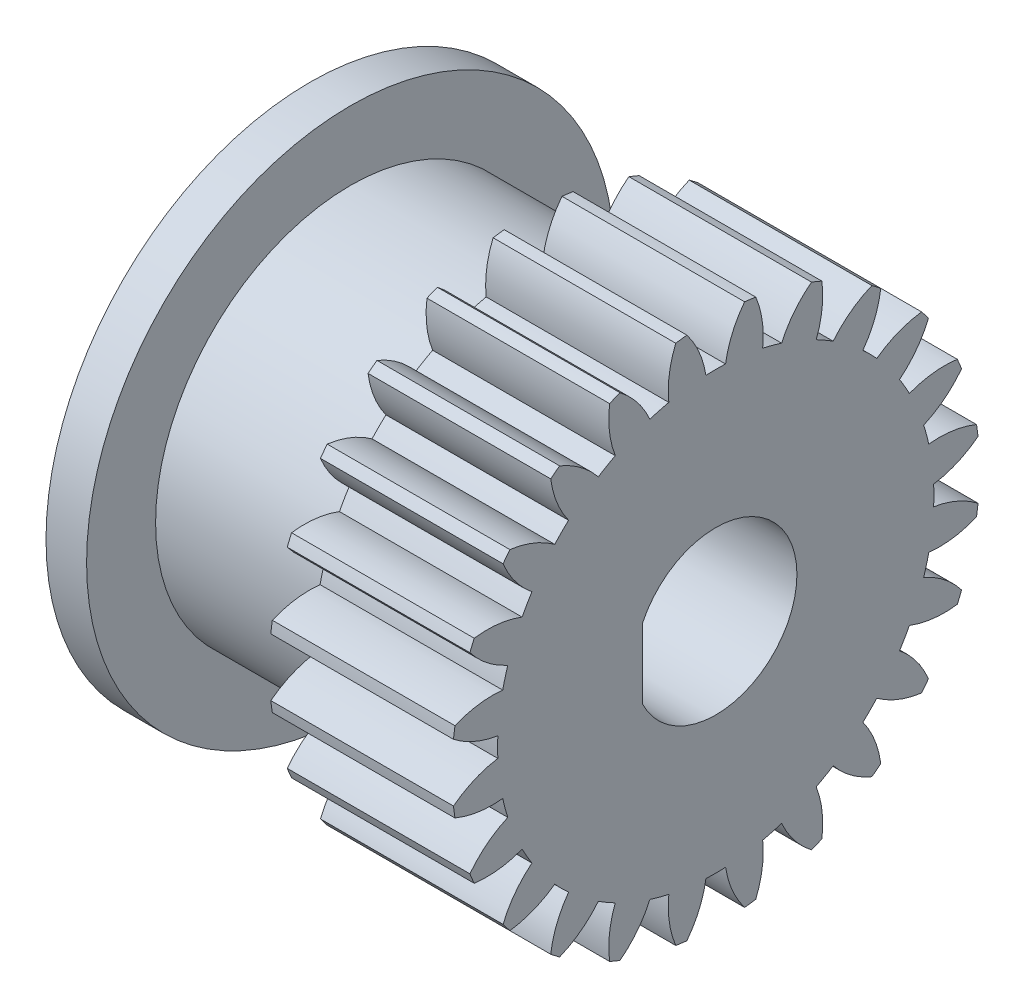
SolidWorks part; units mm, degrees
ref_plane "前视基准面" through (0, 0, 0) normal (0, 0, 1) x (1, 0, 0)
ref_plane "上视基准面" through (0, 0, 0) normal (0, 1, 0) x (1, 0, 0)
ref_plane "右视基准面" through (0, 0, 0) normal (1, 0, 0) x (0, 0, -1)
ref_plane "基准面4" through (0, 0, 0) normal (0, 0, -1) x (-1, 0, 0)
sketch "草图1" plane through (0, 0, 0) normal (0, 0, -1) x (-1, 0, 0)
  line L0 (-4.5, 6.5) -> (-4.5, 0)
  line L1 (-4.5, 0) -> (5.5, 0)
  line L2 (5.5, 0) -> (5.5, 6.5)
  line L3 (5.5, 6.5) -> (4.5, 6.5)
  line L4 (4.5, 6.5) -> (4.5, 4.8)
  line L5 (4.5, 4.8) -> (0, 4.8)
  line L6 (0, 4.8) -> (0, 6.5)
  line L7 (0, 6.5) -> (-4.5, 6.5)
  line L8 (-4.5, 0) -> (5.5, 0) construction
revolve "旋转1" add sketch "草图1" angle 360 about L8
sketch "草图2" plane through (4.5, 0, 0) normal (1, 0, 0) x (0, 0, -1)
  arc A0 (-6.0567, 2.3593) -> (-6.4249, 0.9851) centre (0, 0) ccw
  arc A1 (-6.4249, 0.9851) -> (-5.2482, 1.1561) centre (-5.5023, -1.2304) cw
  arc A2 (-5.2482, 1.1561) -> (-5.1231, 1.6229) centre (0, 0) cw
  arc A3 (-5.1231, 1.6229) -> (-6.0567, 2.3593) centre (-4.1499, 3.8167) cw
extrude "切除-拉伸1" cut sketch "草图2" against normal up to next
sketch "草图3" plane through (4.5, 0, 0) normal (1, 0, 0) x (0, 0, -1)
  arc A0 (-5.2397, 3.8465) -> (-5.951, 2.6144) centre (0, 0) ccw
  arc A1 (-5.951, 2.6144) -> (-4.7701, 2.475) centre (-5.6332, 0.2356) cw
  arc A2 (-4.7701, 2.475) -> (-4.5285, 2.8936) centre (0, 0) cw
  arc A3 (-4.5285, 2.8936) -> (-5.2397, 3.8465) centre (-3.0206, 4.7607) cw
extrude "切除-拉伸2" cut sketch "草图3" against normal up to next
sketch "草图4" plane through (4.5, 0, 0) normal (1, 0, 0) x (0, 0, -1)
  arc A0 (-4.0656, 5.0716) -> (-5.0716, 4.0656) centre (0, 0) ccw
  arc A1 (-5.0716, 4.0656) -> (-3.967, 3.6253) centre (-5.3803, 1.6855) cw
  arc A2 (-3.967, 3.6253) -> (-3.6253, 3.967) centre (0, 0) cw
  arc A3 (-3.6253, 3.967) -> (-4.0656, 5.0716) centre (-1.6855, 5.3803) cw
extrude "切除-拉伸3" cut sketch "草图4" against normal up to next
sketch "草图5" plane through (4.5, 0, 0) normal (1, 0, 0) x (0, 0, -1)
  arc A0 (-3.8465, 5.2397) -> (-2.8936, 4.5285) centre (-4.7607, 3.0206) cw
  arc A1 (-2.8936, 4.5285) -> (-2.475, 4.7701) centre (0, 0) cw
  arc A2 (-2.475, 4.7701) -> (-2.6144, 5.951) centre (-0.2356, 5.6332) cw
  arc A3 (-2.6144, 5.951) -> (-3.8465, 5.2397) centre (0, 0) ccw
extrude "切除-拉伸4" cut sketch "草图5" against normal up to next
sketch "草图6" plane through (4.5, 0, 0) normal (1, 0, 0) x (0, 0, -1)
  arc A0 (-2.3593, 6.0567) -> (-1.6229, 5.1231) centre (-3.8167, 4.1499) cw
  arc A1 (-1.6229, 5.1231) -> (-1.1561, 5.2482) centre (0, 0) cw
  arc A2 (-1.1561, 5.2482) -> (-0.9851, 6.4249) centre (1.2304, 5.5023) cw
  arc A3 (-0.9851, 6.4249) -> (-2.3593, 6.0567) centre (0, 0) ccw
extrude "切除-拉伸5" cut sketch "草图6" against normal up to next
sketch "草图7" plane through (4.5, 0, 0) normal (1, 0, 0) x (0, 0, -1)
  arc A0 (0.7113, 6.461) -> (-0.7113, 6.461) centre (0, 0) ccw
  arc A1 (-0.7113, 6.461) -> (-0.2416, 5.3686) centre (-2.6126, 4.9963) cw
  arc A2 (-0.2416, 5.3686) -> (0.2416, 5.3686) centre (0, 0) cw
  arc A3 (0.2416, 5.3686) -> (0.7113, 6.461) centre (2.6126, 4.9963) cw
extrude "切除-拉伸6" cut sketch "草图7" against normal up to next
sketch "草图8" plane through (4.5, 0, 0) normal (1, 0, 0) x (0, 0, -1)
  arc A0 (2.3593, 6.0567) -> (0.9851, 6.4249) centre (0, 0) ccw
  arc A1 (0.9851, 6.4249) -> (1.1561, 5.2482) centre (-1.2304, 5.5023) cw
  arc A2 (1.1561, 5.2482) -> (1.6229, 5.1231) centre (0, 0) cw
  arc A3 (1.6229, 5.1231) -> (2.3593, 6.0567) centre (3.8167, 4.1499) cw
extrude "切除-拉伸7" cut sketch "草图8" against normal up to next
sketch "草图9" plane through (4.5, 0, 0) normal (1, 0, 0) x (0, 0, -1)
  arc A0 (3.8465, 5.2397) -> (2.6144, 5.951) centre (0, 0) ccw
  arc A1 (2.6144, 5.951) -> (2.475, 4.7701) centre (0.2356, 5.6332) cw
  arc A2 (2.475, 4.7701) -> (2.8936, 4.5285) centre (0, 0) cw
  arc A3 (2.8936, 4.5285) -> (3.8465, 5.2397) centre (4.7607, 3.0206) cw
extrude "切除-拉伸8" cut sketch "草图9" against normal up to next
sketch "草图10" plane through (4.5, 0, 0) normal (1, 0, 0) x (0, 0, -1)
  arc A0 (5.0716, 4.0656) -> (4.0656, 5.0716) centre (0, 0) ccw
  arc A1 (4.0656, 5.0716) -> (3.6253, 3.967) centre (1.6855, 5.3803) cw
  arc A2 (3.6253, 3.967) -> (3.967, 3.6253) centre (0, 0) cw
  arc A3 (3.967, 3.6253) -> (5.0716, 4.0656) centre (5.3803, 1.6855) cw
extrude "切除-拉伸9" cut sketch "草图10" against normal up to next
sketch "草图11" plane through (4.5, 0, 0) normal (1, 0, 0) x (0, 0, -1)
  arc A0 (5.951, 2.6144) -> (5.2397, 3.8465) centre (0, 0) ccw
  arc A1 (5.2397, 3.8465) -> (4.5285, 2.8936) centre (3.0206, 4.7607) cw
  arc A2 (4.5285, 2.8936) -> (4.7701, 2.475) centre (0, 0) cw
  arc A3 (4.7701, 2.475) -> (5.951, 2.6144) centre (5.6332, 0.2356) cw
extrude "切除-拉伸10" cut sketch "草图11" against normal up to next
sketch "草图12" plane through (4.5, 0, 0) normal (1, 0, 0) x (0, 0, -1)
  arc A0 (6.4249, 0.9851) -> (6.0567, 2.3593) centre (0, 0) ccw
  arc A1 (6.0567, 2.3593) -> (5.1231, 1.6229) centre (4.1499, 3.8167) cw
  arc A2 (5.1231, 1.6229) -> (5.2482, 1.1561) centre (0, 0) cw
  arc A3 (5.2482, 1.1561) -> (6.4249, 0.9851) centre (5.5023, -1.2304) cw
extrude "切除-拉伸11" cut sketch "草图12" against normal up to next
sketch "草图13" plane through (4.5, 0, 0) normal (1, 0, 0) x (0, 0, -1)
  arc A0 (6.461, -0.7113) -> (6.461, 0.7113) centre (0, 0) ccw
  arc A1 (6.461, 0.7113) -> (5.3686, 0.2416) centre (4.9963, 2.6126) cw
  arc A2 (5.3686, 0.2416) -> (5.3686, -0.2416) centre (0, 0) cw
  arc A3 (5.3686, -0.2416) -> (6.461, -0.7113) centre (4.9963, -2.6126) cw
extrude "切除-拉伸12" cut sketch "草图13" against normal up to next
sketch "草图14" plane through (4.5, 0, 0) normal (1, 0, 0) x (0, 0, -1)
  arc A0 (6.0567, -2.3593) -> (6.4249, -0.9851) centre (0, 0) ccw
  arc A1 (6.4249, -0.9851) -> (5.2482, -1.1561) centre (5.5023, 1.2304) cw
  arc A2 (5.2482, -1.1561) -> (5.1231, -1.6229) centre (0, 0) cw
  arc A3 (5.1231, -1.6229) -> (6.0567, -2.3593) centre (4.1499, -3.8167) cw
extrude "切除-拉伸13" cut sketch "草图14" against normal up to next
sketch "草图15" plane through (4.5, 0, 0) normal (1, 0, 0) x (0, 0, -1)
  arc A0 (5.2397, -3.8465) -> (5.951, -2.6144) centre (0, 0) ccw
  arc A1 (5.951, -2.6144) -> (4.7701, -2.475) centre (5.6332, -0.2356) cw
  arc A2 (4.7701, -2.475) -> (4.5285, -2.8936) centre (0, 0) cw
  arc A3 (4.5285, -2.8936) -> (5.2397, -3.8465) centre (3.0206, -4.7607) cw
extrude "切除-拉伸14" cut sketch "草图15" against normal up to next
sketch "草图16" plane through (4.5, 0, 0) normal (1, 0, 0) x (0, 0, -1)
  arc A0 (4.0656, -5.0716) -> (5.0716, -4.0656) centre (0, 0) ccw
  arc A1 (5.0716, -4.0656) -> (3.967, -3.6253) centre (5.3803, -1.6855) cw
  arc A2 (3.967, -3.6253) -> (3.6253, -3.967) centre (0, 0) cw
  arc A3 (3.6253, -3.967) -> (4.0656, -5.0716) centre (1.6855, -5.3803) cw
extrude "切除-拉伸15" cut sketch "草图16" against normal up to next
sketch "草图17" plane through (4.5, 0, 0) normal (1, 0, 0) x (0, 0, -1)
  arc A0 (2.6144, -5.951) -> (3.8465, -5.2397) centre (0, 0) ccw
  arc A1 (3.8465, -5.2397) -> (2.8936, -4.5285) centre (4.7607, -3.0206) cw
  arc A2 (2.8936, -4.5285) -> (2.475, -4.7701) centre (0, 0) cw
  arc A3 (2.475, -4.7701) -> (2.6144, -5.951) centre (0.2356, -5.6332) cw
extrude "切除-拉伸16" cut sketch "草图17" against normal up to next
sketch "草图18" plane through (4.5, 0, 0) normal (1, 0, 0) x (0, 0, -1)
  arc A0 (0.9851, -6.4249) -> (2.3593, -6.0567) centre (0, 0) ccw
  arc A1 (2.3593, -6.0567) -> (1.6229, -5.1231) centre (3.8167, -4.1499) cw
  arc A2 (1.6229, -5.1231) -> (1.1561, -5.2482) centre (0, 0) cw
  arc A3 (1.1561, -5.2482) -> (0.9851, -6.4249) centre (-1.2304, -5.5023) cw
extrude "切除-拉伸17" cut sketch "草图18" against normal up to next
sketch "草图19" plane through (4.5, 0, 0) normal (1, 0, 0) x (0, 0, -1)
  arc A0 (-0.7113, -6.461) -> (0.7113, -6.461) centre (0, 0) ccw
  arc A1 (0.7113, -6.461) -> (0.2416, -5.3686) centre (2.6126, -4.9963) cw
  arc A2 (0.2416, -5.3686) -> (-0.2416, -5.3686) centre (0, 0) cw
  arc A3 (-0.2416, -5.3686) -> (-0.7113, -6.461) centre (-2.6126, -4.9963) cw
extrude "切除-拉伸18" cut sketch "草图19" against normal up to next
sketch "草图20" plane through (4.5, 0, 0) normal (1, 0, 0) x (0, 0, -1)
  arc A0 (-2.3593, -6.0567) -> (-0.9851, -6.4249) centre (0, 0) ccw
  arc A1 (-0.9851, -6.4249) -> (-1.1561, -5.2482) centre (1.2304, -5.5023) cw
  arc A2 (-1.1561, -5.2482) -> (-1.6229, -5.1231) centre (0, 0) cw
  arc A3 (-1.6229, -5.1231) -> (-2.3593, -6.0567) centre (-3.8167, -4.1499) cw
extrude "切除-拉伸19" cut sketch "草图20" against normal up to next
sketch "草图21" plane through (4.5, 0, 0) normal (1, 0, 0) x (0, 0, -1)
  arc A0 (-3.8465, -5.2397) -> (-2.6144, -5.951) centre (0, 0) ccw
  arc A1 (-2.6144, -5.951) -> (-2.475, -4.7701) centre (-0.2356, -5.6332) cw
  arc A2 (-2.475, -4.7701) -> (-2.8936, -4.5285) centre (0, 0) cw
  arc A3 (-2.8936, -4.5285) -> (-3.8465, -5.2397) centre (-4.7607, -3.0206) cw
extrude "切除-拉伸20" cut sketch "草图21" against normal up to next
sketch "草图22" plane through (4.5, 0, 0) normal (1, 0, 0) x (0, 0, -1)
  arc A0 (-5.0716, -4.0656) -> (-4.0656, -5.0716) centre (0, 0) ccw
  arc A1 (-4.0656, -5.0716) -> (-3.6253, -3.967) centre (-1.6855, -5.3803) cw
  arc A2 (-3.6253, -3.967) -> (-3.967, -3.6253) centre (0, 0) cw
  arc A3 (-3.967, -3.6253) -> (-5.0716, -4.0656) centre (-5.3803, -1.6855) cw
extrude "切除-拉伸21" cut sketch "草图22" against normal up to next
sketch "草图23" plane through (4.5, 0, 0) normal (1, 0, 0) x (0, 0, -1)
  arc A0 (-5.951, -2.6144) -> (-5.2397, -3.8465) centre (0, 0) ccw
  arc A1 (-5.2397, -3.8465) -> (-4.5285, -2.8936) centre (-3.0206, -4.7607) cw
  arc A2 (-4.5285, -2.8936) -> (-4.7701, -2.475) centre (0, 0) cw
  arc A3 (-4.7701, -2.475) -> (-5.951, -2.6144) centre (-5.6332, -0.2356) cw
extrude "切除-拉伸22" cut sketch "草图23" against normal up to next
sketch "草图24" plane through (4.5, 0, 0) normal (1, 0, 0) x (0, 0, -1)
  arc A0 (-6.4249, -0.9851) -> (-6.0567, -2.3593) centre (0, 0) ccw
  arc A1 (-6.0567, -2.3593) -> (-5.1231, -1.6229) centre (-4.1499, -3.8167) cw
  arc A2 (-5.1231, -1.6229) -> (-5.2482, -1.1561) centre (0, 0) cw
  arc A3 (-5.2482, -1.1561) -> (-6.4249, -0.9851) centre (-5.5023, 1.2304) cw
extrude "切除-拉伸23" cut sketch "草图24" against normal up to next
sketch "草图25" plane through (4.5, 0, 0) normal (1, 0, 0) x (0, 0, -1)
  arc A0 (-6.461, 0.7113) -> (-6.461, -0.7113) centre (0, 0) ccw
  arc A1 (-6.461, -0.7113) -> (-5.3686, -0.2416) centre (-4.9963, -2.6126) cw
  arc A2 (-5.3686, -0.2416) -> (-5.3686, 0.2416) centre (0, 0) cw
  arc A3 (-5.3686, 0.2416) -> (-6.461, 0.7113) centre (-4.9963, 2.6126) cw
extrude "切除-拉伸24" cut sketch "草图25" against normal up to next
sketch "草图26" plane through (-5.5, 0, 0) normal (-1, 0, 0) x (0, 0, 1)
  line L0 (1.8, -0.8718) -> (1.8, 0.8718)
  arc A0 (1.8, 0.8718) -> (1.8, -0.8718) centre (0, 0) ccw
extrude "切除-拉伸25" cut sketch "草图26" against normal through all
